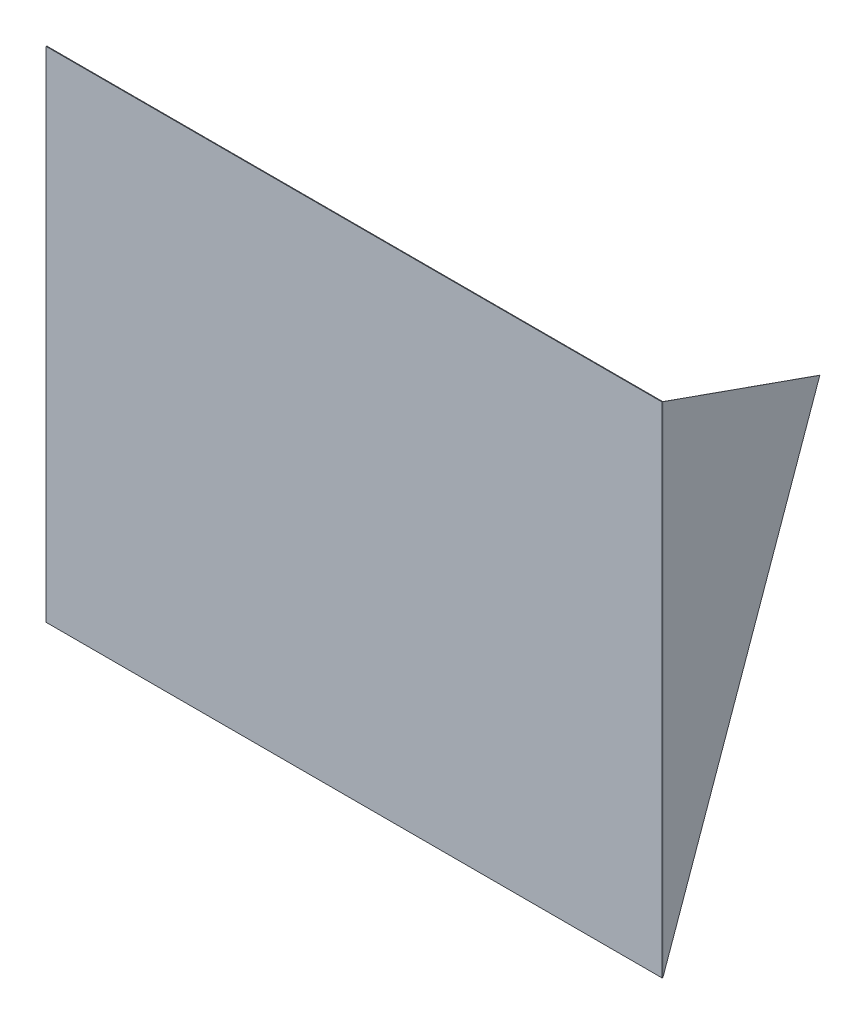
SolidWorks part; units mm, degrees
ref_plane "Спереди" through (0, 0, 0) normal (0, 0, 1) x (1, 0, 0)
ref_plane "Сверху" through (0, 0, 0) normal (0, 1, 0) x (1, 0, 0)
ref_plane "Справа" through (0, 0, 0) normal (1, 0, 0) x (0, 0, -1)
sketch "Эскиз1" plane through (0, 0, 0) normal (0, 0, 1) x (1, 0, 0)
  line L1 (1491.9774, 2689.0387) -> (-7708.0226, 2689.0387)
  line L2 (1491.9774, 2689.0387) -> (1491.9774, -4760.9613)
  line L3 (1491.9774, -4760.9613) -> (-7708.0226, -4760.9613)
  line L4 (-7708.0226, 2689.0387) -> (-7708.0226, -4760.9613)
  dimension "D1" = 9200
  dimension "D2" = 7450
extrude "Бобышка-Вытянуть1" add sketch "Эскиз1" along normal blind 10
sketch "Эскиз2" plane through (1491.9774, 0, 0) normal (1, 0, 0) x (0, 0, -1)
  line L0 (0, -4760.9613) -> (2344.2185, 1858.9074)
  line L1 (2344.2185, 1858.9074) -> (0, 2689.0387)
  line L2 (-10, -4760.9613) -> (-10, 2689.0387) construction
  line L7 (0, -4760.9613) -> (0, 2689.0387)
  line L8 (0, 2689.0387) -> (-10, 2689.0387)
  line L9 (-10, 2689.0387) -> (-10, -4760.9613)
  line L10 (-10, -4760.9613) -> (0, -4760.9613)
  line L11 (0, -4760.9613) -> (0, 2689.0387)
  dimension "D1" = 19.5
  dimension "D2" = 0
extrude "Бобышка-Вытянуть2" add sketch "Эскиз2" along normal blind 1 separate body
